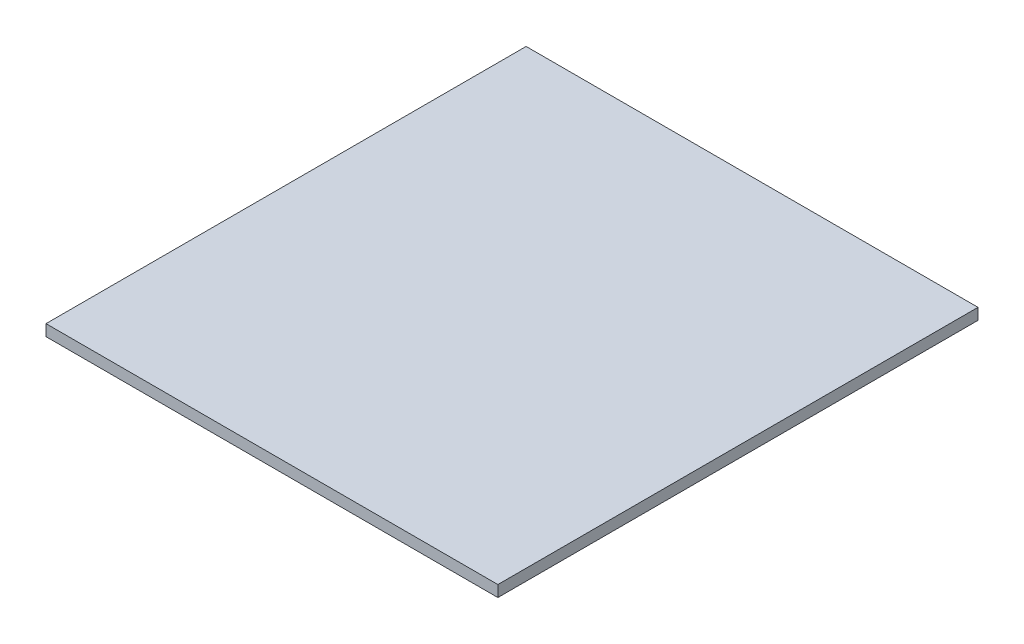
SolidWorks part; units mm, degrees
ref_plane "Front Plane" through (0, 0, 0) normal (0, 0, 1) x (1, 0, 0)
ref_plane "Top Plane" through (0, 0, 0) normal (0, 1, 0) x (1, 0, 0)
ref_plane "Right Plane" through (0, 0, 0) normal (1, 0, 0) x (0, 0, -1)
sketch "Sketch1" plane through (0, 0, 0) normal (0, 1, 0) x (1, 0, 0)
  line L1 (-80, 117.3613) -> (80, 117.3613)
  line L2 (-80, 117.3613) -> (-80, -52.6387)
  line L3 (-80, -52.6387) -> (80, -52.6387)
  line L4 (80, 117.3613) -> (80, -52.6387)
  circle A0 centre (-73, 110.3613) radius 2
  circle A1 centre (-73, -45.6387) radius 2
  circle A2 centre (73, -45.6387) radius 2
  circle A3 centre (73, 110.3613) radius 2
  point P0 (0, 0)
  dimension "D2" = 4
  dimension "D3" = 7
  dimension "D4" = 7
  dimension "D5" = 4
  dimension "D7" = 7
  dimension "D8" = 4
  dimension "D9" = 7
  dimension "D10" = 7
  dimension "D11" = 4
  dimension "D12" = 7
  dimension "D13" = 7
  dimension "D1" = 160
  dimension "D6" = 7
  dimension "D14" = 170
extrude "Boss-Extrude1" add sketch "Sketch1" along normal blind 4 contours L1 L4 L3 L2
